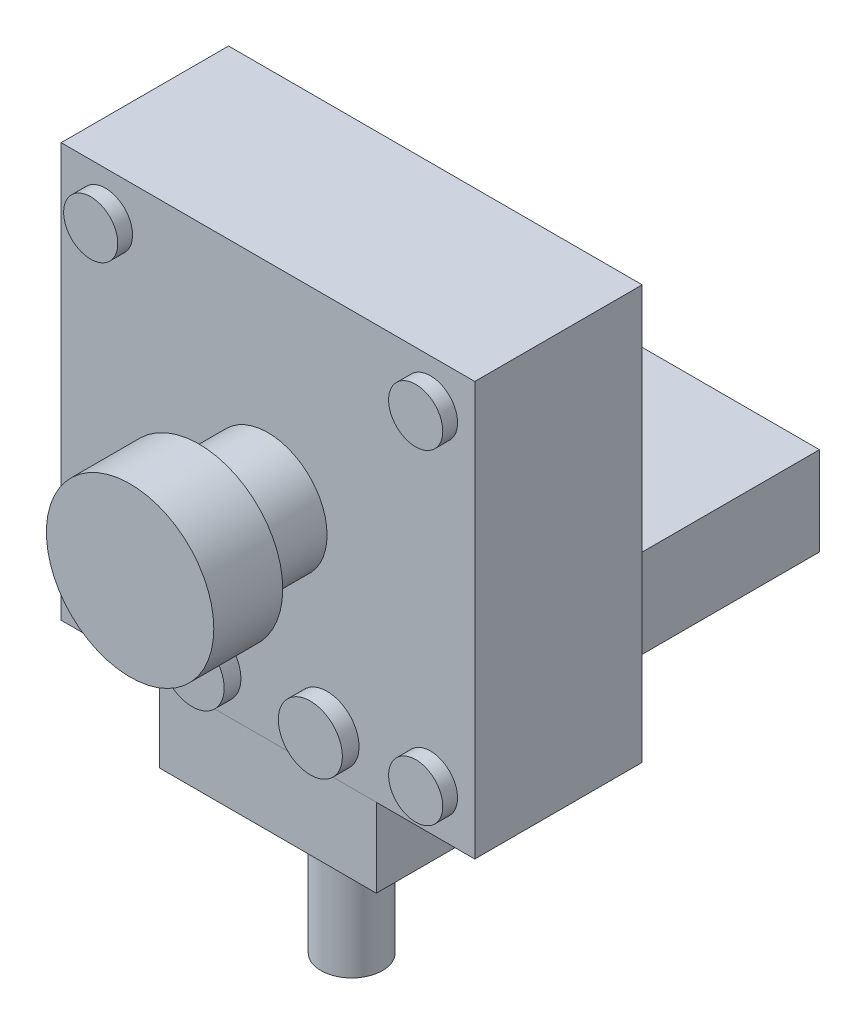
SolidWorks part; units mm, degrees
ref_plane "Front Plane" through (0, 0, 0) normal (0, 0, 1) x (1, 0, 0)
ref_plane "Top Plane" through (0, 0, 0) normal (0, 1, 0) x (1, 0, 0)
ref_plane "Right Plane" through (0, 0, 0) normal (1, 0, 0) x (0, 0, -1)
sketch "Sketch1" plane through (0, 0, 0) normal (0, 0, 1) x (1, 0, 0)
  line L1 (0, 0) -> (42, 0)
  line L2 (0, 0) -> (0, 42)
  line L3 (0, 42) -> (42, 42)
  line L4 (42, 0) -> (42, 42)
  dimension "D1" = 42
  dimension "D2" = 42
extrude "Box" add sketch "Sketch1" along normal blind 17
sketch "Sketch2" plane through (0, 0, 17) normal (0, 0, 1) x (1, 0, 0)
  line L0 (0, 42) -> (42, 0) construction
  circle A0 centre (21, 21) radius 6
  dimension "D1" = 12
extrude "Lens" add sketch "Sketch2" along normal blind 7 separate body
sketch "Sketch3" plane through (0, 0, 24) normal (0, 0, 1) x (1, 0, 0)
  circle A0 centre (21, 21) radius 8.5
  circle A2 centre (21, 21) radius 6 construction
  dimension "D1" = 17
extrude "Lens cap" add sketch "Sketch3" along normal blind 7
sketch "Sketch4" plane through (0, 0, 0) normal (0, -1, 0) x (1, 0, 0)
  line L0 (21, 0) -> (21, 17) construction
  line L1 (0, 0) -> (42, 0) construction
  line L2 (0, 17) -> (42, 17) construction
  line L4 (10, 17) -> (32, 17)
  line L5 (10, 17) -> (10, 0)
  line L6 (10, 0) -> (32, 0)
  line L7 (32, 17) -> (32, 0)
  point P10 (21, 0)
  dimension "D1" = 22
extrude "Adapter" add sketch "Sketch4" along normal blind 8 separate body
sketch "Sketch5" plane through (0, -8, 0) normal (0, -1, 0) x (1, 0, 0)
  line L0 (32, 17) -> (10, 0) construction
  line L1 (10, 17) -> (10, 0) construction
  line L2 (10, 0) -> (32, 0) construction
  circle A0 centre (21, 8.5) radius 3.125
  dimension "D1" = 6.25
extrude "Bolt" add sketch "Sketch5" along normal blind 15
sketch "Sketch6" plane through (0, 0, 0) normal (0, 0, -1) x (-1, 0, 0)
  line L0 (0, 4.5) -> (-42, 4.5) construction
  line L1 (0, 42) -> (0, 0) construction
  line L2 (-42, 0) -> (-42, 42) construction
  line L3 (0, 0) -> (-42, 0) construction
  line L4 (-11.5, 6.25) -> (-30.5, 2.75) construction
  line L5 (-30.5, 2.75) -> (-11.5, 2.75)
  line L6 (-30.5, 2.75) -> (-30.5, 6.25)
  line L7 (-30.5, 6.25) -> (-11.5, 6.25)
  line L8 (-11.5, 2.75) -> (-11.5, 6.25)
  point P12 (-21, 4.5)
  point P13 (-21, 4.5)
  dimension "D1" = 4.5
  dimension "D2" = 19
  dimension "D3" = 3.5
extrude "USB_connector" add sketch "Sketch6" along normal blind 2.5 separate body
sketch "Sketch7" plane through (0, 0, -2.5) normal (0, 0, -1) x (-1, 0, 0)
  line L0 (-11.5, 2.75) -> (-30.5, 6.25) construction
  line L1 (0, 0) -> (-42, 0) construction
  line L2 (-32.5, 0) -> (-9.5, 0)
  line L3 (-32.5, 0) -> (-32.5, 9)
  line L4 (-32.5, 9) -> (-9.5, 9)
  line L5 (-9.5, 0) -> (-9.5, 9)
  line L6 (-32.5, 0) -> (-9.5, 9) construction
  line L7 (-32.5, 9) -> (-9.5, 0) construction
  line L8 (-30.5, 2.75) -> (-11.5, 2.75) construction
  line L9 (-11.5, 2.75) -> (-11.5, 6.25) construction
  point P4 (-21, 4.5)
  dimension "D1" = 2
  dimension "D2" = 2.75
extrude "USB_head" add sketch "Sketch7" along normal blind 25
sketch "Sketch8" plane through (0, 0, 17) normal (0, 0, 1) x (1, 0, 0)
  line L0 (21, 42) -> (21, 0) construction
  line L1 (42, 42) -> (0, 42) construction
  line L2 (0, 0) -> (42, 0) construction
  line L3 (0, 21) -> (42, 21) construction
  line L4 (0, 42) -> (0, 0) construction
  line L5 (42, 0) -> (42, 42) construction
  circle A0 centre (4.5, 4.5) radius 2.75
  circle A1 centre (37.5, 4.5) radius 2.75
  circle A2 centre (37.5, 37.5) radius 2.75
  circle A3 centre (4.5, 37.5) radius 2.75
  dimension "D1" = 16.5
  dimension "D2" = 5.5
  dimension "D3" = 16.5
extrude "House_screws" add sketch "Sketch8" along normal blind 1.5 and the other way offset from surface (18.5 mm away) 1.5 other way up to face at (21, 21, 0)
sketch "Sketch9" plane through (0, 0, 17) normal (0, 0, 1) x (1, 0, 0)
  line L0 (21, 0) -> (21, 42) construction
  line L1 (0, 0) -> (42, 0) construction
  line L2 (42, 42) -> (0, 42) construction
  circle A0 centre (15, 4) radius 3.25
  circle A1 centre (27, 4) radius 3.25
  dimension "D1" = 6.5
  dimension "D2" = 6
  dimension "D3" = 4
extrude "Adapter_skrews" add sketch "Sketch9" along normal blind 1.7
